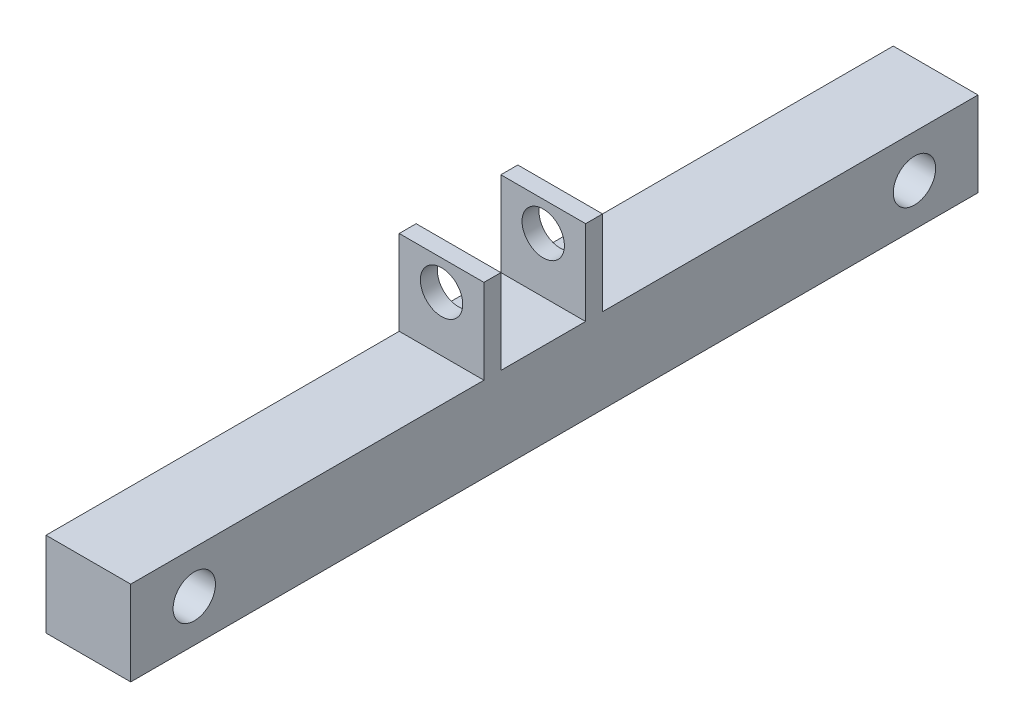
SolidWorks part; units mm, degrees
ref_plane "Front Plane" through (0, 0, 0) normal (0, 0, 1) x (1, 0, 0)
ref_plane "Top Plane" through (0, 0, 0) normal (0, 1, 0) x (1, 0, 0)
ref_plane "Right Plane" through (0, 0, 0) normal (1, 0, 0) x (0, 0, -1)
sketch "Sketch1" plane through (0, 0, 0) normal (0, 0, 1) x (1, 0, 0)
  line L1 (-10, 10) -> (10, 10)
  line L2 (-10, 10) -> (-10, -10)
  line L3 (-10, -10) -> (10, -10)
  line L4 (10, 10) -> (10, -10)
  line L5 (-10, 10) -> (10, -10) construction
  line L6 (-10, -10) -> (10, 10) construction
  circle A0 centre (0, 0) radius 5 construction
  point P1 (0, 0)
  dimension "D3" = 10
  dimension "D1" = 20
  dimension "D2" = 20
extrude "Boss-Extrude1" add sketch "Sketch1" along normal blind 200
sketch "Sketch2" plane through (0, 10, 0) normal (0, 1, 0) x (1, 0, 0)
  line L0 (0, -200) -> (0, 0) construction
  line L1 (10, -200) -> (-10, -200) construction
  line L2 (-10, -100) -> (10, -100) construction
  line L3 (-10, -200) -> (-10, 0) construction
  line L4 (10, -200) -> (10, 0) construction
  circle A0 centre (0, -100) radius 7.5
  dimension "D1" = 15
sketch "Sketch3" plane through (-10, 0, 0) normal (-1, 0, 0) x (0, 0, 1)
  line L0 (0, 0) -> (200, 0) construction
  line L1 (200, 10) -> (200, -10) construction
  line L2 (0, 10) -> (0, -10) construction
  line L3 (100, 10) -> (100, -10) construction
  line L4 (200, 10) -> (0, 10) construction
  line L5 (200, -10) -> (0, -10) construction
  circle A0 centre (15, 0) radius 5
  circle A1 centre (185, 0) radius 5
  dimension "D1" = 10
  dimension "D2" = 15
extrude "Cut-Extrude1" cut sketch "Sketch3" against normal blind 57
sketch "Sketch4" plane through (0, 10, 0) normal (0, 1, 0) x (1, 0, 0)
  line L0 (-10, -100) -> (-10, -92.6259)
  line L1 (-10, -200) -> (-10, 0) construction
  line L2 (-10, -92.6259) -> (10, -92.6259)
  line L3 (10, -200) -> (10, 0) construction
  line L4 (10, -92.6259) -> (10, -112.6259)
  line L5 (10, -112.6259) -> (-10, -112.6259)
  line L6 (-10, -112.6259) -> (-10, -100)
  line L7 (10, -116.6259) -> (-10, -116.6259)
  line L8 (-10, -116.6259) -> (-10, -112.6259)
  line L9 (10, -116.6259) -> (10, -112.6259)
  line L10 (10, -88.6259) -> (-10, -88.6259)
  line L11 (-10, -88.6259) -> (-10, -92.6259)
  line M8 (-10, 0) -> (-10, -200)
  line M10 (10, -200) -> (10, 0)
  dimension "D1" = 20
  dimension "D2" = 4
  dimension "D3" = 4
extrude "Boss-Extrude2" add sketch "Sketch4" along normal blind 20 contours L7 L5 M10 M8 | L10 L2 M10 M8
sketch "Sketch5" plane through (0, 0, 88.6259) normal (0, 0, -1) x (-1, 0, 0)
  line L0 (0, 30) -> (0, 10) construction
  line L1 (-10, 30) -> (10, 30) construction
  line L2 (7.5, 10) -> (-7.5, 10) construction
  line L3 (0, 10) -> (0, 23) construction
  line L4 (0, 23) -> (10, 23) construction
  line L6 (10, 23) -> (-10, 23) construction
  line L9 (-10, 10) -> (10, 10) construction
  circle A0 centre (0, 23) radius 5
  dimension "D1" = 10
  dimension "D2" = 13
extrude "Cut-Extrude2" cut sketch "Sketch5" against normal blind 49
